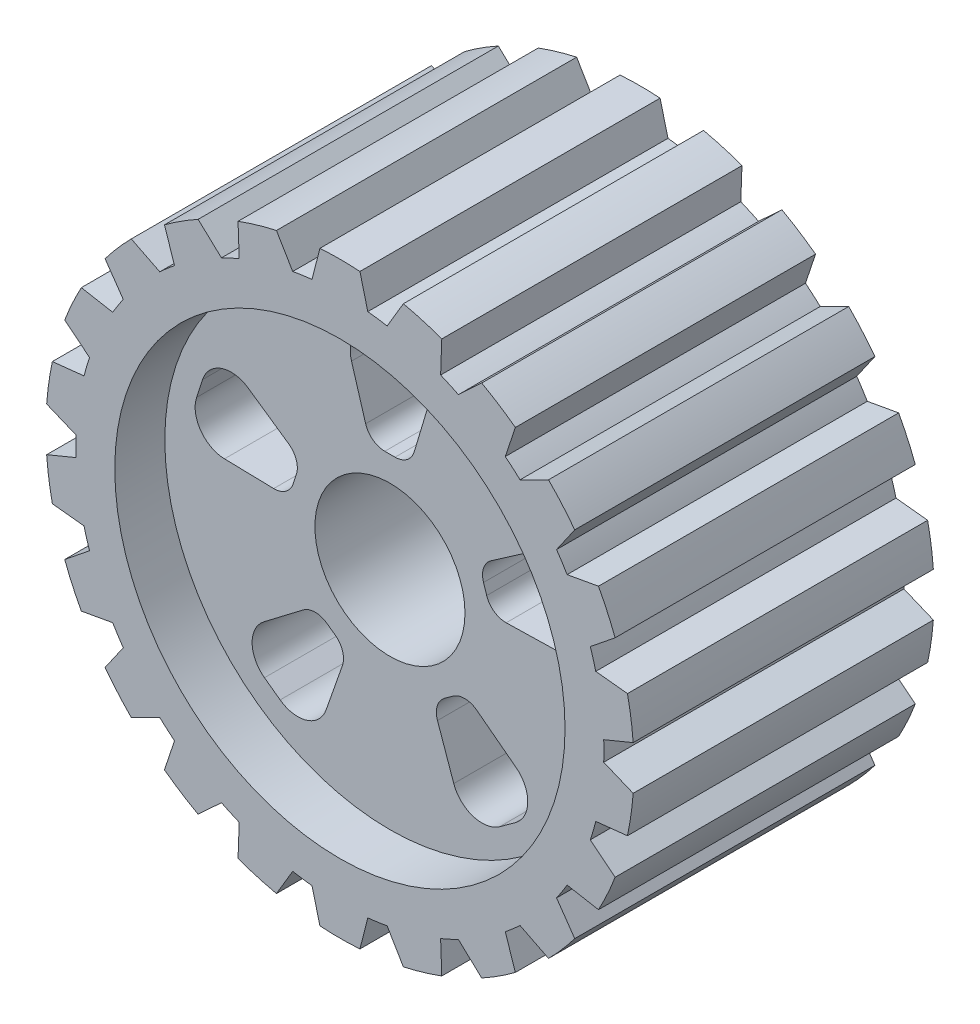
SolidWorks part; units mm, degrees
ref_plane "Спереди" through (0, 0, 0) normal (0, 0, 1) x (1, 0, 0)
ref_plane "Сверху" through (0, 0, 0) normal (0, 1, 0) x (1, 0, 0)
ref_plane "Справа" through (0, 0, 0) normal (1, 0, 0) x (0, 0, -1)
sketch "Эскиз1" plane through (0, 0, 0) normal (0, 0, 1) x (1, 0, 0)
  line L0 (0, 0) -> (0, 32.9831) construction
  line L1 (-2, 29.3209) -> (-2.7867, 26.2344)
  line L2 (2, 29.3209) -> (2.7867, 26.2344)
  line L3 (6.3417, 28.6966) -> (4.7172, 25.9568)
  line L4 (10.1796, 27.5697) -> (10.0649, 24.3866)
  line L5 (14.1696, 25.7476) -> (11.839, 23.5764)
  line L6 (17.5346, 23.585) -> (16.5277, 20.5632)
  line L7 (20.8495, 20.7126) -> (18.0017, 19.286)
  line L8 (23.469, 17.6896) -> (21.6516, 15.0738)
  line L9 (25.8404, 13.9996) -> (22.706, 13.4331)
  line L10 (27.502, 10.3611) -> (25.0213, 8.3633)
  line L11 (28.7378, 6.1524) -> (25.5708, 6.4919)
  line L12 (29.3071, 2.1932) -> (26.364, 0.9752)
  line L13 (29.3071, -2.1932) -> (26.364, -0.9752)
  line L14 (28.7378, -6.1524) -> (25.5708, -6.4919)
  line L15 (27.502, -10.3611) -> (25.0213, -8.3633)
  line L16 (25.8404, -13.9996) -> (22.706, -13.4331)
  line L17 (23.469, -17.6896) -> (21.6516, -15.0738)
  line L18 (20.8495, -20.7126) -> (18.0017, -19.286)
  line L19 (17.5346, -23.585) -> (16.5277, -20.5632)
  line L20 (14.1696, -25.7476) -> (11.839, -23.5764)
  line L21 (10.1796, -27.5697) -> (10.0649, -24.3866)
  line L22 (6.3417, -28.6966) -> (4.7172, -25.9568)
  line L23 (2, -29.3209) -> (2.7867, -26.2344)
  line L24 (-2, -29.3209) -> (-2.7867, -26.2344)
  line L25 (-6.3417, -28.6966) -> (-4.7172, -25.9568)
  line L26 (-10.1796, -27.5697) -> (-10.0649, -24.3866)
  line L27 (-14.1696, -25.7476) -> (-11.839, -23.5764)
  line L28 (-17.5346, -23.585) -> (-16.5277, -20.5632)
  line L29 (-20.8495, -20.7126) -> (-18.0017, -19.286)
  line L30 (-23.469, -17.6896) -> (-21.6516, -15.0738)
  line L31 (-25.8404, -13.9996) -> (-22.706, -13.4331)
  line L32 (-27.502, -10.3611) -> (-25.0213, -8.3633)
  line L33 (-28.7378, -6.1524) -> (-25.5708, -6.4919)
  line L34 (-29.3071, -2.1932) -> (-26.364, -0.9752)
  line L35 (-29.3071, 2.1932) -> (-26.364, 0.9752)
  line L36 (-28.7378, 6.1524) -> (-25.5708, 6.4919)
  line L37 (-27.502, 10.3611) -> (-25.0213, 8.3633)
  line L38 (-25.8404, 13.9996) -> (-22.706, 13.4331)
  line L39 (-23.469, 17.6896) -> (-21.6516, 15.0738)
  line L40 (-20.8495, 20.7126) -> (-18.0017, 19.286)
  line L41 (-17.5346, 23.585) -> (-16.5277, 20.5632)
  line L42 (-14.1696, 25.7476) -> (-11.839, 23.5764)
  line L43 (-10.1796, 27.5697) -> (-10.0649, 24.3866)
  line L44 (-6.3417, 28.6966) -> (-4.7172, 25.9568)
  arc A0 (2, 29.3209) -> (-2, 29.3209) centre (0, 0) ccw
  arc A1 (-2.7867, 26.2344) -> (-3.76, 26.1127) centre (0, 0) ccw
  arc A2 (2.7867, 26.2344) -> (3.76, 26.1127) centre (0, 0) cw
  arc A3 (4.7172, 25.9568) -> (3.7491, 26.1143) centre (0, 0) ccw
  arc A4 (10.0649, 24.3866) -> (10.9645, 23.9956) centre (0, 0) cw
  arc A5 (10.1796, 27.5697) -> (6.3417, 28.6966) centre (0, 0) ccw
  arc A6 (11.839, 23.5764) -> (10.9545, 24.0002) centre (0, 0) ccw
  arc A7 (16.5277, 20.5632) -> (17.2807, 19.9346) centre (0, 0) cw
  arc A8 (17.5346, 23.585) -> (14.1696, 25.7476) centre (0, 0) ccw
  arc A9 (18.0017, 19.286) -> (17.2724, 19.9418) centre (0, 0) ccw
  arc A10 (21.6516, 15.0738) -> (22.1969, 14.2586) centre (0, 0) cw
  arc A11 (23.469, 17.6896) -> (20.8495, 20.7126) centre (0, 0) ccw
  arc A12 (22.706, 13.4331) -> (22.191, 14.2678) centre (0, 0) ccw
  arc A13 (25.0213, 8.3633) -> (25.3149, 7.4274) centre (0, 0) cw
  arc A14 (27.502, 10.3611) -> (25.8404, 13.9996) centre (0, 0) ccw
  arc A15 (25.5708, 6.4919) -> (25.3118, 7.438) centre (0, 0) ccw
  arc A16 (26.364, 0.9752) -> (26.382, -0.0055) centre (0, 0) cw
  arc A17 (29.3071, 2.1932) -> (28.7378, 6.1524) centre (0, 0) ccw
  arc A18 (26.364, -0.9752) -> (26.382, 0.0055) centre (0, 0) ccw
  arc A19 (25.5708, -6.4919) -> (25.3118, -7.438) centre (0, 0) cw
  arc A20 (28.7378, -6.1524) -> (29.3071, -2.1932) centre (0, 0) ccw
  arc A21 (25.0213, -8.3633) -> (25.3149, -7.4274) centre (0, 0) ccw
  arc A22 (22.706, -13.4331) -> (22.191, -14.2678) centre (0, 0) cw
  arc A23 (25.8404, -13.9996) -> (27.502, -10.3611) centre (0, 0) ccw
  arc A24 (21.6516, -15.0738) -> (22.1969, -14.2586) centre (0, 0) ccw
  arc A25 (18.0017, -19.286) -> (17.2724, -19.9418) centre (0, 0) cw
  arc A26 (20.8495, -20.7126) -> (23.469, -17.6896) centre (0, 0) ccw
  arc A27 (16.5277, -20.5632) -> (17.2807, -19.9346) centre (0, 0) ccw
  arc A28 (11.839, -23.5764) -> (10.9545, -24.0002) centre (0, 0) cw
  arc A29 (14.1696, -25.7476) -> (17.5346, -23.585) centre (0, 0) ccw
  arc A30 (10.0649, -24.3866) -> (10.9645, -23.9956) centre (0, 0) ccw
  arc A31 (4.7172, -25.9568) -> (3.7491, -26.1143) centre (0, 0) cw
  arc A32 (6.3417, -28.6966) -> (10.1796, -27.5697) centre (0, 0) ccw
  arc A33 (2.7867, -26.2344) -> (3.76, -26.1127) centre (0, 0) ccw
  arc A34 (-2.7867, -26.2344) -> (-3.76, -26.1127) centre (0, 0) cw
  arc A35 (-2, -29.3209) -> (2, -29.3209) centre (0, 0) ccw
  arc A36 (-4.7172, -25.9568) -> (-3.7491, -26.1143) centre (0, 0) ccw
  arc A37 (-10.0649, -24.3866) -> (-10.9645, -23.9956) centre (0, 0) cw
  arc A38 (-10.1796, -27.5697) -> (-6.3417, -28.6966) centre (0, 0) ccw
  arc A39 (-11.839, -23.5764) -> (-10.9545, -24.0002) centre (0, 0) ccw
  arc A40 (-16.5277, -20.5632) -> (-17.2807, -19.9346) centre (0, 0) cw
  arc A41 (-17.5346, -23.585) -> (-14.1696, -25.7476) centre (0, 0) ccw
  arc A42 (-18.0017, -19.286) -> (-17.2724, -19.9418) centre (0, 0) ccw
  arc A43 (-21.6516, -15.0738) -> (-22.1969, -14.2586) centre (0, 0) cw
  arc A44 (-23.469, -17.6896) -> (-20.8495, -20.7126) centre (0, 0) ccw
  arc A45 (-22.706, -13.4331) -> (-22.191, -14.2678) centre (0, 0) ccw
  arc A46 (-25.0213, -8.3633) -> (-25.3149, -7.4274) centre (0, 0) cw
  arc A47 (-27.502, -10.3611) -> (-25.8404, -13.9996) centre (0, 0) ccw
  arc A48 (-25.5708, -6.4919) -> (-25.3118, -7.438) centre (0, 0) ccw
  arc A49 (-26.364, -0.9752) -> (-26.382, 0.0055) centre (0, 0) cw
  arc A50 (-29.3071, -2.1932) -> (-28.7378, -6.1524) centre (0, 0) ccw
  arc A51 (-26.364, 0.9752) -> (-26.382, -0.0055) centre (0, 0) ccw
  arc A52 (-25.5708, 6.4919) -> (-25.3118, 7.438) centre (0, 0) cw
  arc A53 (-28.7378, 6.1524) -> (-29.3071, 2.1932) centre (0, 0) ccw
  arc A54 (-25.0213, 8.3633) -> (-25.3149, 7.4274) centre (0, 0) ccw
  arc A55 (-22.706, 13.4331) -> (-22.191, 14.2678) centre (0, 0) cw
  arc A56 (-25.8404, 13.9996) -> (-27.502, 10.3611) centre (0, 0) ccw
  arc A57 (-21.6516, 15.0738) -> (-22.1969, 14.2586) centre (0, 0) ccw
  arc A58 (-18.0017, 19.286) -> (-17.2724, 19.9418) centre (0, 0) cw
  arc A59 (-20.8495, 20.7126) -> (-23.469, 17.6896) centre (0, 0) ccw
  arc A60 (-16.5277, 20.5632) -> (-17.2807, 19.9346) centre (0, 0) ccw
  arc A61 (-11.839, 23.5764) -> (-10.9545, 24.0002) centre (0, 0) cw
  arc A62 (-14.1696, 25.7476) -> (-17.5346, 23.585) centre (0, 0) ccw
  arc A63 (-10.0649, 24.3866) -> (-10.9645, 23.9956) centre (0, 0) ccw
  arc A64 (-4.7172, 25.9568) -> (-3.7491, 26.1143) centre (0, 0) cw
  arc A65 (-6.3417, 28.6966) -> (-10.1796, 27.5697) centre (0, 0) ccw
  circle A66 centre (0, 0) radius 22.5
  point P137 (0, 0)
  dimension "D1" = 29.389
  dimension "D2" = 26.382
  dimension "D7" = 45
  dimension "D3" = 14.3
  dimension "D4" = 4
  dimension "D5" = 3.76
  dimension "D6" = 22
extrude "Бобышка-Вытянуть1" add sketch "Эскиз1" along normal mid plane 30
sketch "Эскиз2" plane through (0, 0, 0) normal (0, 0, 1) x (1, 0, 0)
  line L0 (0, 0) -> (0, 22.5) construction
  line L1 (-0.9679, 20) -> (0.9679, 20)
  line L2 (3.8414, 16.138) -> (2.4276, 11.4253)
  line L3 (0.5119, 10) -> (-0.5119, 10)
  line L4 (-3.8414, 16.138) -> (-2.4276, 11.4253)
  line L5 (18.722, 7.1009) -> (19.3202, 5.2598)
  line L6 (14.1611, 8.6403) -> (10.1159, 5.8394)
  line L7 (9.6688, 2.6033) -> (9.3524, 3.5771)
  line L8 (16.5352, 1.3335) -> (11.6163, 1.2218)
  line L9 (12.5388, -15.6114) -> (10.9727, -16.7493)
  line L10 (12.5934, -10.798) -> (8.6796, -7.8164)
  line L11 (5.4637, -8.3911) -> (6.292, -7.7893)
  line L12 (6.3779, -15.3138) -> (4.7517, -10.6702)
  line L13 (-10.9727, -16.7493) -> (-12.5388, -15.6114)
  line L14 (-6.3779, -15.3138) -> (-4.7517, -10.6702)
  line L15 (-6.292, -7.7893) -> (-5.4637, -8.3911)
  line L16 (-12.5934, -10.798) -> (-8.6796, -7.8164)
  line L17 (-19.3202, 5.2598) -> (-18.722, 7.1009)
  line L18 (-16.5352, 1.3335) -> (-11.6163, 1.2218)
  line L19 (-9.3524, 3.5771) -> (-9.6688, 2.6033)
  line L20 (-14.1611, 8.6403) -> (-10.1159, 5.8394)
  circle A0 centre (0, 0) radius 22.5 construction
  circle A1 centre (0, 0) radius 22.5
  circle A2 centre (0, 0) radius 7.5
  arc A3 (0.9679, 20) -> (3.8414, 16.138) centre (0.9679, 17) cw
  arc A4 (2.4276, 11.4253) -> (0.5119, 10) centre (0.5119, 12) cw
  arc A5 (-2.4276, 11.4253) -> (-0.5119, 10) centre (-0.5119, 12) ccw
  arc A6 (-0.9679, 20) -> (-3.8414, 16.138) centre (-0.9679, 17) ccw
  arc A7 (19.3202, 5.2598) -> (16.5352, 1.3335) centre (16.4671, 4.3328) cw
  arc A8 (18.722, 7.1009) -> (14.1611, 8.6403) centre (15.8689, 6.1738) ccw
  arc A9 (10.1159, 5.8394) -> (9.3524, 3.5771) centre (11.2545, 4.1951) ccw
  arc A10 (11.6163, 1.2218) -> (9.6688, 2.6033) centre (11.5709, 3.2213) cw
  arc A11 (10.9727, -16.7493) -> (6.3779, -15.3138) centre (9.2093, -14.3222) cw
  arc A12 (12.5388, -15.6114) -> (12.5934, -10.798) centre (10.7754, -13.1844) ccw
  arc A13 (8.6796, -7.8164) -> (6.292, -7.7893) centre (7.4676, -9.4073) ccw
  arc A14 (4.7517, -10.6702) -> (5.4637, -8.3911) centre (6.6393, -10.0091) cw
  arc A15 (-12.5388, -15.6114) -> (-12.5934, -10.798) centre (-10.7754, -13.1844) cw
  arc A16 (-10.9727, -16.7493) -> (-6.3779, -15.3138) centre (-9.2093, -14.3222) ccw
  arc A17 (-4.7517, -10.6702) -> (-5.4637, -8.3911) centre (-6.6393, -10.0091) ccw
  arc A18 (-8.6796, -7.8164) -> (-6.292, -7.7893) centre (-7.4676, -9.4073) cw
  arc A19 (-18.722, 7.1009) -> (-14.1611, 8.6403) centre (-15.8689, 6.1738) cw
  arc A20 (-19.3202, 5.2598) -> (-16.5352, 1.3335) centre (-16.4671, 4.3328) ccw
  arc A21 (-11.6163, 1.2218) -> (-9.6688, 2.6033) centre (-11.5709, 3.2213) ccw
  arc A22 (-10.1159, 5.8394) -> (-9.3524, 3.5771) centre (-11.2545, 4.1951) cw
  point P11 (5, 20)
  point P14 (2, 10)
  point P16 (0, 10)
  point P21 (0, 20)
  point P71 (0, 0)
  dimension "D1" = 15
  dimension "D6" = 3
  dimension "D7" = 2
  dimension "D9" = 15
  dimension "D2" = 10
  dimension "D3" = 10
  dimension "D4" = 2
  dimension "D5" = 5
  dimension "D8" = 5
extrude "Бобышка-Вытянуть2" add sketch "Эскиз2" along normal mid plane 20
